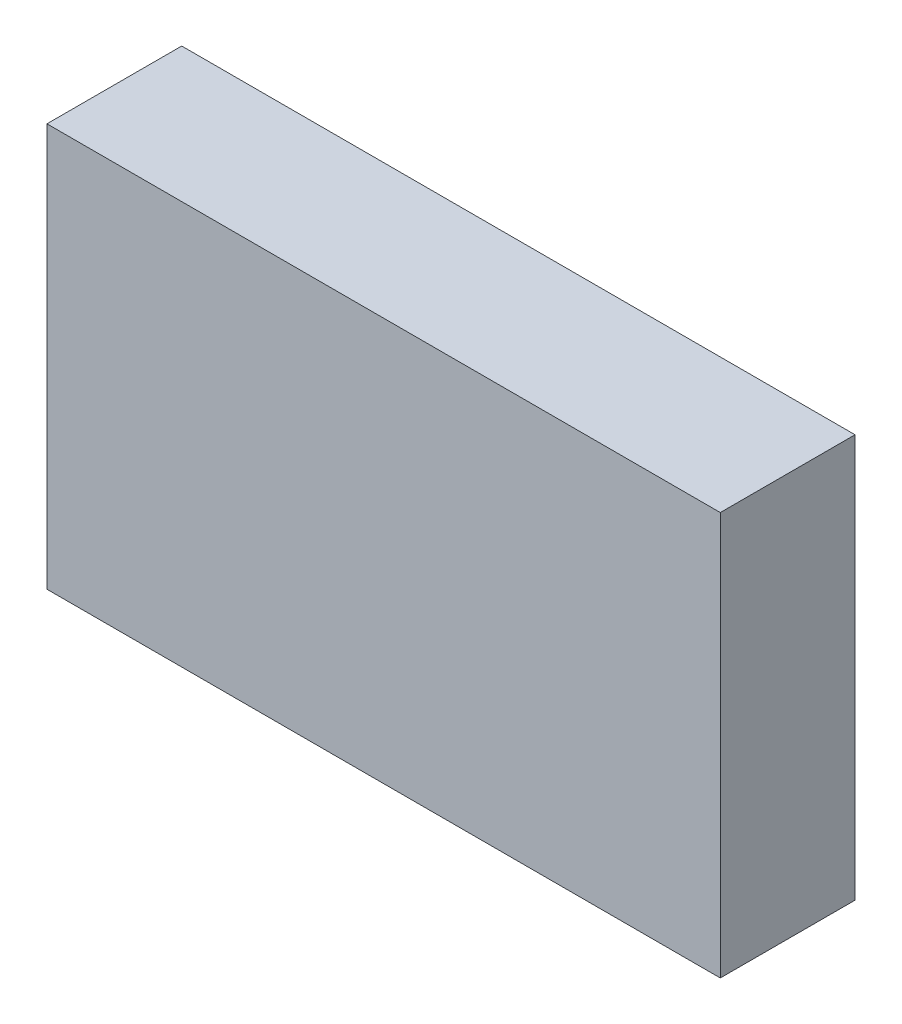
SolidWorks part; units mm, degrees
ref_plane "Ebene vorne" through (0, 0, 0) normal (0, 0, 1) x (1, 0, 0)
ref_plane "Ebene oben" through (0, 0, 0) normal (0, 1, 0) x (1, 0, 0)
ref_plane "Ebene rechts" through (0, 0, 0) normal (1, 0, 0) x (0, 0, -1)
sketch "Skizze1" plane through (0, 0, 0) normal (0, 0, 1) x (1, 0, 0)
  line L0 (-2.4984, 1.5084) -> (2.4984, 1.5084)
  line L1 (2.4984, 1.5084) -> (2.4984, -1.483)
  line L2 (2.4984, -1.483) -> (-2.4984, -1.483)
  line L3 (-2.4984, -1.483) -> (-2.4984, 1.5084)
extrude "Component_Outline" add sketch "Skizze1" along normal blind 1 separate body
sketch3d "3D-Skizze1"
  line L0 (0, 0, 0) -> (1, 0, 0)
  line L1 (0, 0, 0) -> (0, 1, 0)
  line L2 (0, 0, 0) -> (0, 0, 1)
  point P0 (0, 0, 0)
